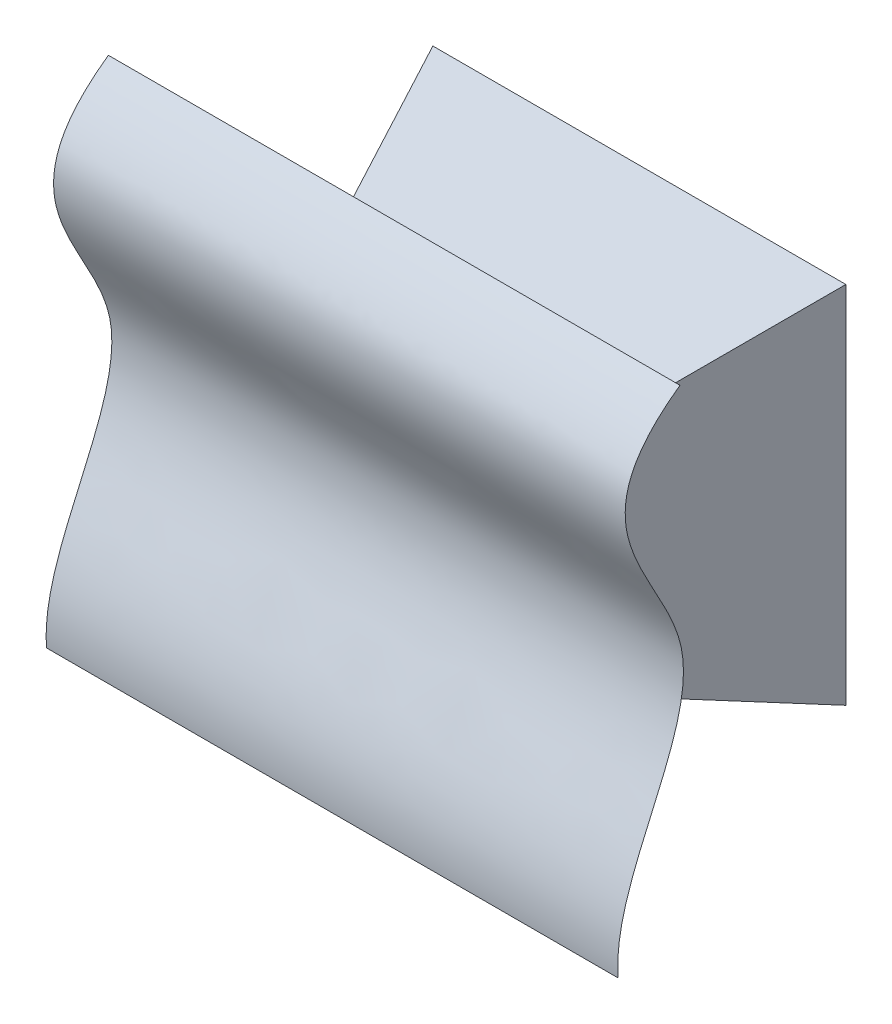
SolidWorks part; units mm, degrees
ref_plane "Спереди" through (0, 0, 0) normal (0, 0, 1) x (1, 0, 0)
ref_plane "Сверху" through (0, 0, 0) normal (0, 1, 0) x (1, 0, 0)
ref_plane "Справа" through (0, 0, 0) normal (1, 0, 0) x (0, 0, -1)
sketch "Эскиз1_fr" plane through (0, 0, 0) normal (0, 0, 1) x (1, 0, 0)
  line L1 (0, 0) -> (43.3507, 0)
  line L2 (0, 0) -> (0, -38.2597)
  line L3 (0, -38.2597) -> (43.3507, -38.2597)
  line L4 (43.3507, 0) -> (43.3507, -38.2597)
extrude "Бобышка-Вытянуть1" add sketch "Эскиз1_fr" along normal blind 20 draft 20
sketch "Эскиз1_rt" plane through (0, 0, 0) normal (1, 0, 0) x (0, 0, -1)
  spline S0 degree 3 poles (-24.0617, 6.19) (-36.3175, -2.5174) (-13.7833, -17.8971) (-31.3159, -35.3189) (-30.545, -44.4497) knots 0 0 0 0 0.484609 1 1 1 1
  point P2 (0, 0)
surface "Поверхность-Вытянуть2" sketch "Эскиз1_rt" parameters "D1"=50, "D2"=10
